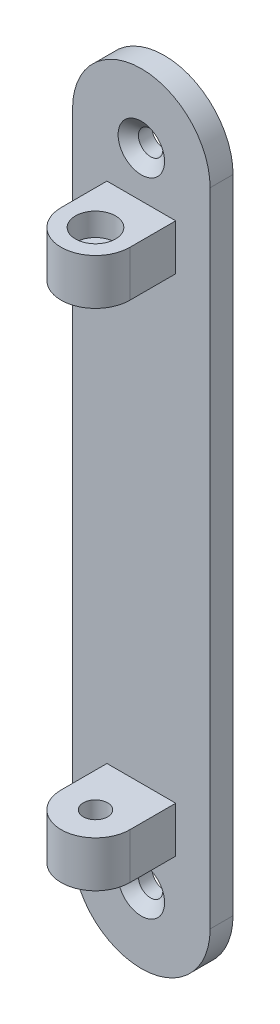
SolidWorks part; units mm, degrees
material "Plain Carbon Steel"
ref_plane "Front Plane" through (0, 0, 0) normal (0, 0, 1) x (1, 0, 0)
ref_plane "Top Plane" through (0, 0, 0) normal (0, 1, 0) x (1, 0, 0)
ref_plane "Right Plane" through (0, 0, 0) normal (1, 0, 0) x (0, 0, -1)
sketch "Sketch1" plane through (0, 0, 0) normal (0, 0, 1) x (1, 0, 0)
  line L0 (0, 0) -> (38.1, 0)
  line L1 (38.1, 0) -> (38.1, 88.9)
  line L2 (0, 88.9) -> (0, 0)
  arc A0 (38.1, 88.9) -> (0, 88.9) centre (19.05, 88.9) ccw
  dimension "D1" = 88.9
  dimension "D2" = 19.05
extrude "Boss-Extrude1" add sketch "Sketch1" along normal blind 6.35
hole_wizard "CSK for 1/4 Flat Head Machine Screw (100)1" positions "Sketch2" profile "Sketch3" countersink size "1/4" standard "ANSI Inch" end condition up to next
sketch "Sketch2" plane through (0, 0, 6.35) normal (0, 0, 1) x (1, 0, 0)
  point P0 (19.05, 88.9)
sketch "Sketch3" plane through (19.05, 88.9, 6.35) normal (1, 0, 0) x (0, -1, 0)
  line L0 (0, 0) -> (0, 6.35)
  line L1 (0, 6.35) -> (3.3782, 6.35)
  line L2 (3.3782, 6.35) -> (3.3782, 2.5682)
  line L3 (3.3782, 2.5682) -> (6.4389, 0)
  line L5 (6.4389, 0) -> (0, 0)
  line L6 (-3.3782, 2.5682) -> (-6.4389, 0) construction
  line L11 (0, -6.35) -> (0, 107.95) construction
  dimension "Thru Hole Dia." = 6.7564
  dimension "Thru Hole Depth" = 6.35
  dimension "Near C'Sink Dia." = 12.8778
  dimension "Near C'Sink Angle" = 100
sketch "Sketch5" plane through (0, 0, 6.35) normal (0, 0, 1) x (1, 0, 0)
  line L0 (19.05, 107.95) -> (19.05, 0) construction
  line L1 (0, 0) -> (38.1, 0) construction
  line L3 (9.525, 76.2) -> (28.575, 76.2)
  line L4 (9.525, 76.2) -> (9.525, 63.5)
  line L5 (9.525, 63.5) -> (28.575, 63.5)
  line L6 (28.575, 76.2) -> (28.575, 63.5)
  line L7 (9.525, 76.2) -> (28.575, 63.5) construction
  line L8 (9.525, 63.5) -> (28.575, 76.2) construction
  arc A0 (38.1, 88.9) -> (0, 88.9) centre (19.05, 88.9) ccw construction
  point P7 (19.05, 69.85)
  point P12 (0, 0)
  point P13 (0, 0)
  point P14 (-43.3794, 80.4466)
  point P15 (0, 0)
  dimension "D1" = 19.05
  dimension "D2" = 12.7
  dimension "D3" = 63.5
extrude "Boss-Extrude2" add sketch "Sketch5" along normal blind 12.7
sketch "Sketch6" plane through (0, 76.2, 0) normal (0, 1, 0) x (1, 0, 0)
  line L0 (9.525, -19.05) -> (28.575, -19.05)
  arc A0 (28.575, -19.05) -> (9.525, -19.05) centre (19.05, -19.05) cw
extrude "Boss-Extrude3" add sketch "Sketch6" against normal up to surface (12.7 mm away) up to face at (19.05, 63.5, 12.7)
hole_wizard "CBORE for 1/4 Socket Head Cap Screw1" positions "Sketch7" profile "Sketch8" counterbore size "1/4" standard "ANSI Inch"
sketch "Sketch7" plane through (0, 76.2, 0) normal (0, 1, 0) x (1, 0, 0)
  point P0 (19.05, -19.05)
  point P5 (0, 0)
sketch "Sketch8" plane through (19.05, 76.2, 19.05) normal (1, 0, 0) x (0, 0, 1)
  line L0 (0, 0) -> (0, 14.7298)
  line L1 (0, 14.7298) -> (3.3782, 12.7)
  line L2 (3.3782, 12.7) -> (3.3782, 6.35)
  line L3 (3.3782, 6.35) -> (5.5562, 6.35)
  line L4 (5.5562, 6.35) -> (5.5562, 0)
  line L5 (5.5562, 0) -> (0, 0)
  line L10 (0, 14.7298) -> (-3.3782, 12.7) construction
  line L11 (0, -6.35) -> (0, 107.95) construction
  dimension "Hole Dia." = 6.7564
  dimension "Hole Depth" = 12.7
  dimension "C'Bore Dia." = 11.1125
  dimension "C'Bore Depth" = 6.35
  dimension "Drill Angle" = 118
mirror "Mirror1" about plane through (0, 0, 6.35) normal (0, 1, 0) of bodies 105
